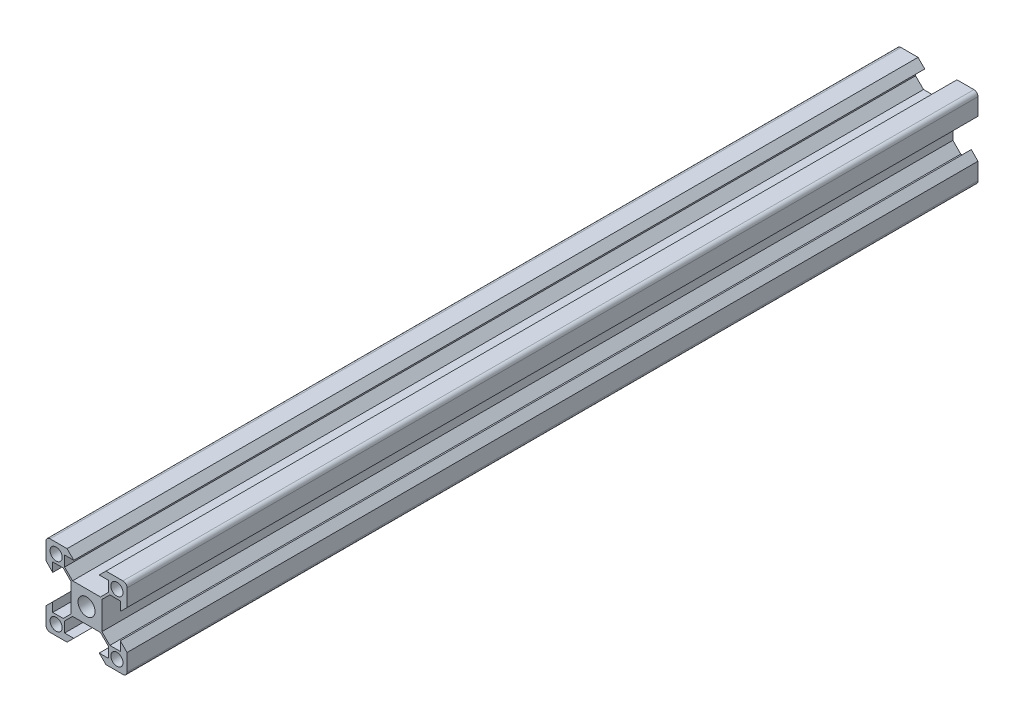
SolidWorks part; units mm, degrees
material "铝管"
ref_plane "前视基准面" through (0, 0, 0) normal (0, 0, 1) x (1, 0, 0)
ref_plane "上视基准面" through (0, 0, 0) normal (0, 1, 0) x (1, 0, 0)
ref_plane "右视基准面" through (0, 0, 0) normal (1, 0, 0) x (0, 0, -1)
sketch "草图1" plane through (0, 0, 0) normal (0, 0, 1) x (1, 0, 0)
  line L0 (0, 0) -> (-40.5659, 40.5659) construction
  line L1 (0, 0) -> (0, 75.5033) construction
  line L2 (-10, 10) -> (-10, 4.8)
  line L3 (-10, 4.8) -> (-8.34, 3.14)
  line L4 (-8.34, 3.14) -> (-8.34, 5.4)
  line L5 (-5.7536, 5.4) -> (-3.8, 3.4464)
  line L6 (-3.8, 3.4464) -> (-3.8, -3.4464)
  line L7 (-3.8, 0) -> (15.6715, 0) construction
  line L8 (-5.4, 8.34) -> (-5.4, 5.7536)
  line L9 (-3.4464, 3.8) -> (3.4464, 3.8)
  line L10 (-5.4, 5.7536) -> (-3.4464, 3.8)
  line L11 (-3.14, 8.34) -> (-5.4, 8.34)
  line L12 (-8.34, 5.4) -> (-5.7536, 5.4)
  line L13 (-4.8, 10) -> (-3.14, 8.34)
  line L14 (-10, 10) -> (-4.8, 10)
  line L15 (-10, -10) -> (-4.8, -10)
  line L16 (-4.8, -10) -> (-3.14, -8.34)
  line L17 (-8.34, -5.4) -> (-5.7536, -5.4)
  line L18 (-3.14, -8.34) -> (-5.4, -8.34)
  line L19 (-5.4, -5.7536) -> (-3.4464, -3.8)
  line L20 (-3.4464, -3.8) -> (3.4464, -3.8)
  line L21 (-5.4, -8.34) -> (-5.4, -5.7536)
  line L22 (-5.7536, -5.4) -> (-3.8, -3.4464)
  line L23 (-8.34, -3.14) -> (-8.34, -5.4)
  line L24 (-10, -4.8) -> (-8.34, -3.14)
  line L25 (-10, -10) -> (-10, -4.8)
  line L26 (10, -10) -> (10, -4.8)
  line L27 (10, -4.8) -> (8.34, -3.14)
  line L28 (8.34, -3.14) -> (8.34, -5.4)
  line L29 (5.7536, -5.4) -> (3.8, -3.4464)
  line L30 (5.4, -8.34) -> (5.4, -5.7536)
  line L31 (5.4, -5.7536) -> (3.4464, -3.8)
  line L32 (3.14, -8.34) -> (5.4, -8.34)
  line L33 (8.34, -5.4) -> (5.7536, -5.4)
  line L34 (4.8, -10) -> (3.14, -8.34)
  line L35 (10, -10) -> (4.8, -10)
  line L36 (10, 10) -> (4.8, 10)
  line L37 (4.8, 10) -> (3.14, 8.34)
  line L38 (8.34, 5.4) -> (5.7536, 5.4)
  line L39 (3.14, 8.34) -> (5.4, 8.34)
  line L40 (5.4, 5.7536) -> (3.4464, 3.8)
  line L41 (5.4, 8.34) -> (5.4, 5.7536)
  line L42 (3.8, 3.4464) -> (3.8, -3.4464)
  line L43 (5.7536, 5.4) -> (3.8, 3.4464)
  line L44 (8.34, 3.14) -> (8.34, 5.4)
  line L45 (10, 4.8) -> (8.34, 3.14)
  line L46 (10, 10) -> (10, 4.8)
  circle A0 centre (-7.5, 7.5) radius 1.5
  circle A1 centre (0, 0) radius 2.1
  circle A2 centre (-7.5, -7.5) radius 1.5
  circle A3 centre (7.5, -7.5) radius 1.5
  circle A4 centre (7.5, 7.5) radius 1.5
  point P54 (0, -3.8)
  point P64 (0, 3.8)
  dimension "D6" = 3
  dimension "D7" = 7.5
  dimension "D9" = 4.2
  dimension "D1" = 45
  dimension "D2" = 4.8
  dimension "D3" = 3.8
  dimension "D4" = 10
  dimension "D5" = 5.4
  dimension "D8" = 3.14
  dimension "D10" = 10
  dimension "D11" = 0.5
extrude "凸台-拉伸1" add sketch "草图1" along normal mid plane 210
fillet "圆角1" radius 1 4 edges at (-10, -10, 0) (10, -10, 0) (-10, 10, 0) (10, 10, 0)
